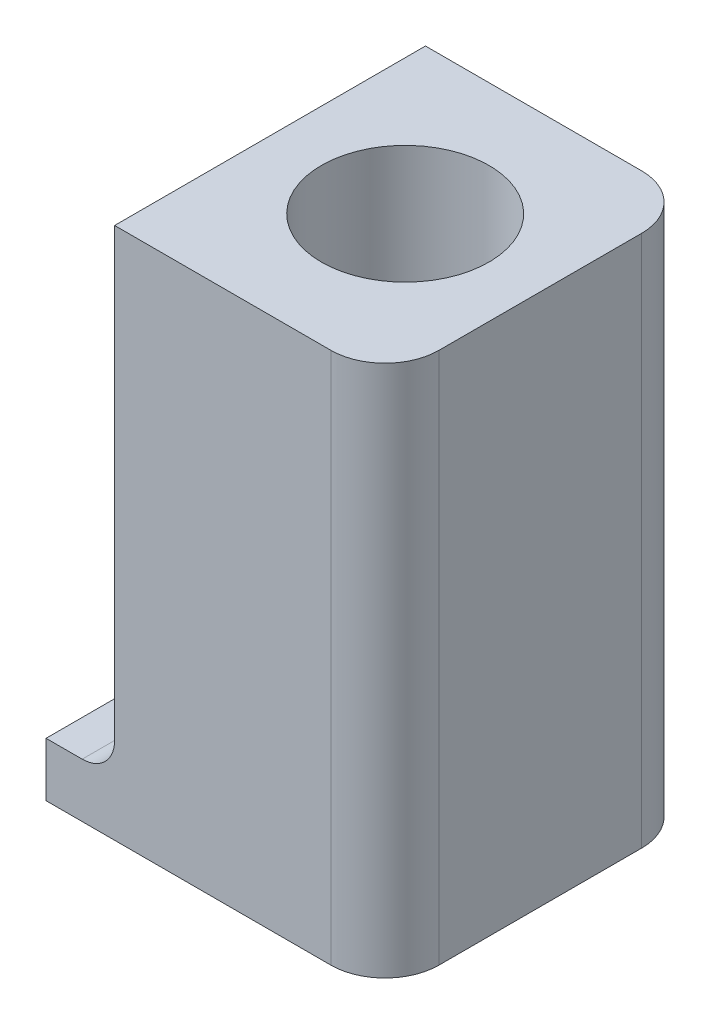
SolidWorks part; units mm, degrees
ref_plane "Front Plane" through (0, 0, 0) normal (0, 0, 1) x (1, 0, 0)
ref_plane "Top Plane" through (0, 0, 0) normal (0, 1, 0) x (1, 0, 0)
ref_plane "Right Plane" through (0, 0, 0) normal (1, 0, 0) x (0, 0, -1)
sketch "Sketch1" plane through (0, 0, 0) normal (0, 1, 0) x (1, 0, 0)
  line L0 (0, 0) -> (0, 4.9523) construction
  line L1 (0, 4.9523) -> (0, 0) construction
  line L2 (0, 0) -> (2.8355, 0) construction
  circle A0 centre (0, 0) radius 13.97
  circle A2 centre (0, 9.5) radius 1.275
  circle A3 centre (9.5, 0) radius 1.275
  circle A4 centre (0, -9.5) radius 1.275
  circle A5 centre (-9.5, 0) radius 1.275
  dimension "D2" = 27.94
  dimension "D3" = 2.55
extrude "Boss-Extrude1" add sketch "Sketch1" along normal blind 3.048
sketch "Sketch2" plane through (0, 3.048, 0) normal (0, 1, 0) x (1, 0, 0)
  line L1 (-96.52, -14.605) -> (96.52, -14.605)
  line L2 (-101.6, -9.525) -> (-101.6, 9.525)
  line L3 (-96.52, 14.605) -> (96.52, 14.605)
  line L4 (101.6, -9.525) -> (101.6, 9.525)
  line L5 (-101.6, -14.605) -> (101.6, 14.605) construction
  line L6 (-101.6, 14.605) -> (101.6, -14.605) construction
  circle A0 centre (-88.9, 0) radius 7.874
  circle A1 centre (88.9, 0) radius 7.874
  arc A3 (96.52, 14.605) -> (101.6, 9.525) centre (96.52, 9.525) cw
  arc A4 (96.52, -14.605) -> (101.6, -9.525) centre (96.52, -9.525) ccw
  arc A5 (-96.52, -14.605) -> (-101.6, -9.525) centre (-96.52, -9.525) cw
  arc A6 (-101.6, 9.525) -> (-96.52, 14.605) centre (-96.52, 9.525) cw
  circle A7 centre (9.5, 0) radius 1.275 construction
  circle A8 centre (0, 9.5) radius 1.275 construction
  circle A9 centre (-9.5, 0) radius 1.275 construction
  circle A10 centre (0, -9.5) radius 1.275 construction
  circle A11 centre (9.5, 0) radius 1.275
  circle A12 centre (0, 9.5) radius 1.275
  circle A13 centre (-9.5, 0) radius 1.275
  circle A14 centre (0, -9.5) radius 1.275
  point P0 (0, 0)
  dimension "D2" = 15.748
  dimension "D3" = 15.748
  dimension "D8" = 5.08
  dimension "D1" = 29.21
  dimension "D4" = 88.9
  dimension "D6" = 12.7
  dimension "D7" = 12.7
extrude "Boss-Extrude2" add sketch "Sketch2" along normal blind 46.99 and the other way through all
sketch "Sketch5" plane through (0, 0, -14.605) normal (0, 0, -1) x (-1, 0, 0)
  line L0 (-101.6, 0) -> (-101.6, 50.038)
  line L1 (-101.6, 50.038) -> (-76.2, 50.038)
  line L2 (-96.52, 50.038) -> (96.52, 50.038) construction
  line L3 (-76.2, 50.038) -> (-76.2, 5.08)
  line L4 (-76.2, 5.08) -> (76.2, 5.08)
  line L5 (0, 5.08) -> (0, 0)
  line L6 (101.6, 0) -> (-101.6, 0)
  line L7 (76.2, 50.038) -> (76.2, 5.08)
  line L8 (101.6, 50.038) -> (76.2, 50.038)
  line L9 (101.6, 0) -> (101.6, 50.038)
  line M8 (96.52, 50.038) -> (-96.52, 50.038)
  dimension "D1" = 25.4
  dimension "D2" = 5.08
extrude "Cut-Extrude2" cut sketch "Sketch5" against normal through all contours L7 L3 L4 M8
sketch "Sketch6" plane through (0, 0, 0) normal (0, -1, 0) x (1, 0, 0)
  circle A0 centre (-88.9, 0) radius 8.89
  circle A1 centre (-88.9, 0) radius 4.191
  circle A2 centre (88.9, 0) radius 8.89
  circle A3 centre (88.9, 0) radius 4.191
  dimension "D1" = 8.382
  dimension "D2" = 8.382
extrude "Boss-Extrude3" add sketch "Sketch6" against normal blind 4.572
fillet "Fillet2" radius 3.048 2 edges at (76.2, 5.08, 0) (-76.2, 5.08, 0)
sketch "Sketch7" plane through (0, 0, -14.605) normal (0, 0, -1) x (-1, 0, 0)
  line L1 (-69.7544, -2.7271) -> (129.9534, -2.7271)
  line L2 (-69.7544, -2.7271) -> (-69.7544, 56.1342)
  line L3 (-69.7544, 56.1342) -> (129.9534, 56.1342)
  line L4 (129.9534, -2.7271) -> (129.9534, 56.1342)
extrude "Cut-Extrude3" cut sketch "Sketch7" against normal through all
